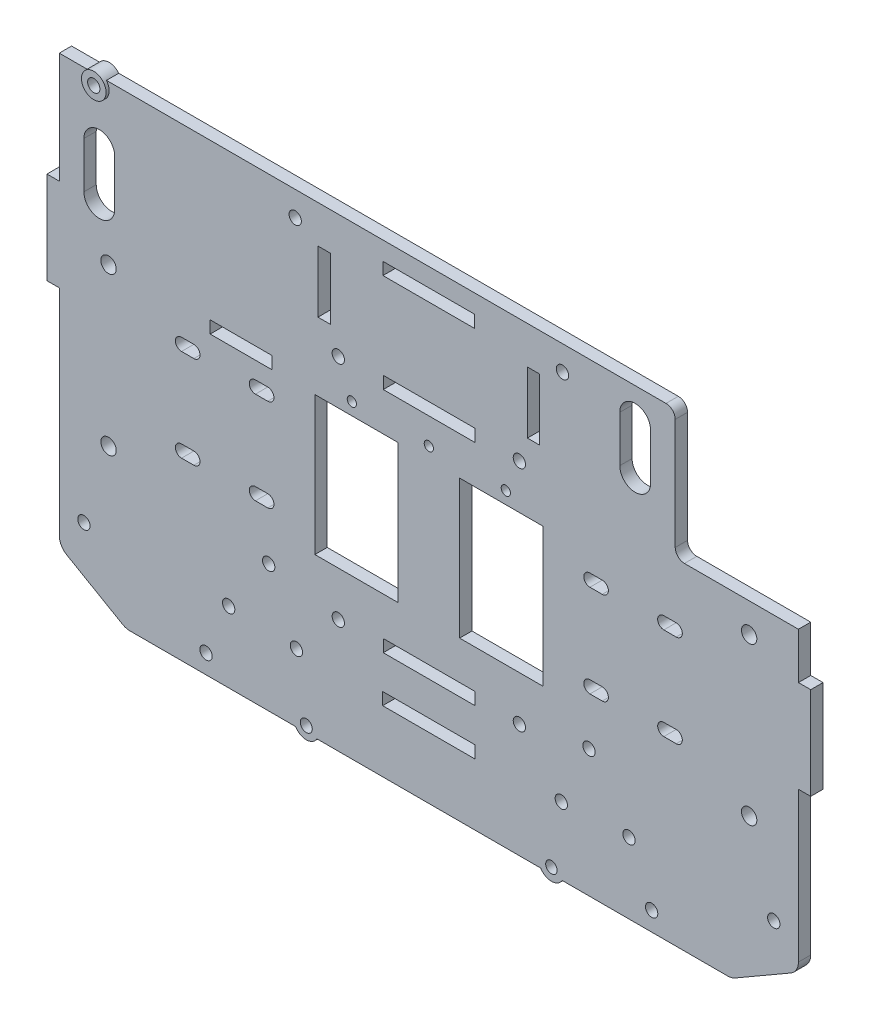
SolidWorks part; units mm, degrees
ref_plane "Front Plane" through (0, 0, 0) normal (0, 0, 1) x (1, 0, 0)
ref_plane "Top Plane" through (0, 0, 0) normal (0, 1, 0) x (1, 0, 0)
ref_plane "Right Plane" through (0, 0, 0) normal (1, 0, 0) x (0, 0, -1)
sketch "Sketch1" plane through (0, 0, 0) normal (0, 0, 1) x (1, 0, 0)
  line L1 (-120, 75.5) -> (120, 75.5)
  line L2 (-120, 75.5) -> (-120, -75.5)
  line L3 (-120, -75.5) -> (120, -75.5)
  line L4 (120, 75.5) -> (120, -75.5)
  dimension "D1" = 240
  dimension "D2" = 151
  dimension "D3" = 75.5
  dimension "D4" = 120
extrude "Boss-Extrude1" add sketch "Sketch1" along normal blind 4
sketch "Sketch2" plane through (0, 0, 0) normal (0, 0, -1) x (-1, 0, 0)
  line L4 (10, 21) -> (37, 21)
  line L5 (37, 21) -> (37, -24)
  line L6 (37, -24) -> (10, -24)
  line L7 (10, -24) -> (10, 21)
  line L8 (0, 0) -> (-98.0945, 0) construction
  line L9 (-120, 75.5) -> (120, 75.5) construction
  line L10 (120, -75.5) -> (-120, -75.5) construction
  line L11 (0, 75.5) -> (0, -75.5) construction
  line L14 (-10, -24) -> (-10, 21)
  line L15 (-37, -24) -> (-10, -24)
  line L16 (-37, 21) -> (-37, -24)
  line L17 (-10, 21) -> (-37, 21)
  dimension "D1" = 45
  dimension "D2" = 27
  dimension "D3" = 21
  dimension "D4" = 10
extrude "Cut-Extrude1" cut sketch "Sketch2" against normal blind 10
sketch "Sketch11" plane through (0, 0, 0) normal (0, 0, -1) x (-1, 0, 0)
  line L0 (0, 0) -> (-153.5827, 0) construction
  line L1 (0, 0) -> (0, 92.8663) construction
  line L2 (-120, 75.5) -> (120, 75.5) construction
  line L3 (20, 16) -> (-27, 16)
  line L4 (20, 16) -> (20, 75.5)
  line L5 (20, 75.5) -> (-27, 75.5)
  line L6 (-27, 16) -> (-27, 75.5)
  dimension "D1" = 16
  dimension "D2" = 20
  dimension "D3" = 47
extrude "Cut-Extrude8" [suppressed] cut sketch "Sketch11" against normal blind 10
sketch "Sketch12" plane through (0, 0, 0) normal (0, 0, -1) x (-1, 0, 0)
  line L0 (0, 0) -> (0, 113.3526) construction
  line L1 (0, 0) -> (164.3438, 0) construction
  circle A0 centre (23, 65) radius 2
  circle A1 centre (23, 45) radius 2
  dimension "D1" = 4
  dimension "D2" = 4
  dimension "D3" = 23
  dimension "D6" = 20
  dimension "D7" = 65
extrude "Cut-Extrude9" [suppressed] cut sketch "Sketch12" against normal blind 5
sketch "Sketch13" [suppressed] plane through (0, 0, 0) normal (0, 0, -1) x (-1, 0, 0)
  line L0 (0, 0) -> (61.643, 0) construction
  line L1 (0, 0) -> (0, 63.8684) construction
  circle A0 centre (23, 65) radius 4
  circle A1 centre (23, 45) radius 4
  circle A2 centre (23, 65) radius 2
  circle A3 centre (23, 45) radius 2
  dimension "D1" = 8
  dimension "D2" = 8
  dimension "D3" = 4
  dimension "D4" = 4
extrude "Boss-Extrude5" [suppressed] add sketch "Sketch13" against normal blind 5
ref_plane "Plane1" [suppressed] through (3.5, 0, 0) normal (1, 0, 0) x (0, 0, -1)
mirror "Mirror1" [suppressed] about plane through (3.5, 0, 0) normal (1, 0, 0)
sketch "Sketch14" plane through (0, 0, 0) normal (0, 0, -1) x (-1, 0, 0)
  line L0 (-37, -1.5) -> (-94.1401, -1.5) construction
  line L1 (-37, 21) -> (-37, -24) construction
  line L2 (-37, -1.5) -> (-37, 9.4006) construction
  line L3 (-56.3, 13.46) -> (-52.3, 13.46) construction
  line L4 (-56.3, 15.46) -> (-52.3, 15.46)
  line L5 (-56.3, 11.46) -> (-52.3, 11.46)
  line L6 (-80.3, 13.46) -> (-76.3, 13.46) construction
  line L7 (-80.3, 15.46) -> (-76.3, 15.46)
  line L8 (-80.3, 11.46) -> (-76.3, 11.46)
  line L9 (-80.3, -16.54) -> (-76.3, -16.54) construction
  line L10 (-80.3, -14.54) -> (-76.3, -14.54)
  line L11 (-80.3, -18.54) -> (-76.3, -18.54)
  line L12 (-56.3, -16.54) -> (-52.3, -16.54) construction
  line L13 (-56.3, -14.54) -> (-52.3, -14.54)
  line L14 (-56.3, -18.54) -> (-52.3, -18.54)
  line L15 (0, 0) -> (0, -41.609) construction
  line L16 (37, -1.5) -> (94.1401, -1.5) construction
  line L17 (56.3, -16.54) -> (52.3, -16.54) construction
  line L18 (56.3, -14.54) -> (52.3, -14.54)
  line L19 (56.3, -18.54) -> (52.3, -18.54)
  line L20 (80.3, -16.54) -> (76.3, -16.54) construction
  line L21 (80.3, -14.54) -> (76.3, -14.54)
  line L22 (80.3, -18.54) -> (76.3, -18.54)
  line L23 (80.3, 13.46) -> (76.3, 13.46) construction
  line L24 (80.3, 15.46) -> (76.3, 15.46)
  line L25 (80.3, 11.46) -> (76.3, 11.46)
  line L26 (56.3, 13.46) -> (52.3, 13.46) construction
  line L27 (56.3, 15.46) -> (52.3, 15.46)
  line L28 (56.3, 11.46) -> (52.3, 11.46)
  arc A0 (56.3, -14.54) -> (56.3, -18.54) centre (56.3, -16.54) cw
  arc A2 (52.3, -18.54) -> (52.3, -14.54) centre (52.3, -16.54) cw
  arc A4 (80.3, -14.54) -> (80.3, -18.54) centre (80.3, -16.54) cw
  arc A6 (76.3, -18.54) -> (76.3, -14.54) centre (76.3, -16.54) cw
  arc A8 (-56.3, 15.46) -> (-56.3, 11.46) centre (-56.3, 13.46) ccw
  arc A9 (-52.3, 11.46) -> (-52.3, 15.46) centre (-52.3, 13.46) ccw
  arc A10 (-80.3, 15.46) -> (-80.3, 11.46) centre (-80.3, 13.46) ccw
  arc A11 (-76.3, 11.46) -> (-76.3, 15.46) centre (-76.3, 13.46) ccw
  arc A12 (-80.3, -14.54) -> (-80.3, -18.54) centre (-80.3, -16.54) ccw
  arc A13 (-76.3, -18.54) -> (-76.3, -14.54) centre (-76.3, -16.54) ccw
  arc A14 (-56.3, -14.54) -> (-56.3, -18.54) centre (-56.3, -16.54) ccw
  arc A15 (-52.3, -18.54) -> (-52.3, -14.54) centre (-52.3, -16.54) ccw
  arc A16 (80.3, 15.46) -> (80.3, 11.46) centre (80.3, 13.46) cw
  arc A17 (76.3, 11.46) -> (76.3, 15.46) centre (76.3, 13.46) cw
  arc A18 (56.3, 15.46) -> (56.3, 11.46) centre (56.3, 13.46) cw
  arc A19 (52.3, 11.46) -> (52.3, 15.46) centre (52.3, 13.46) cw
  point P9 (54.3, -16.54)
  point P15 (-54.3, 13.46)
  point P22 (-78.3, 13.46)
  point P27 (-78.3, -16.54)
  point P34 (-54.3, -16.54)
  point P47 (78.3, -16.54)
  point P54 (78.3, 13.46)
  point P61 (54.3, 13.46)
  dimension "D2" = 14.96
  dimension "D3" = 15.04
  dimension "D4" = 41.3
  dimension "D5" = 4
  dimension "D6" = 4
  dimension "D7" = 4
  dimension "D8" = 4
  dimension "D9" = 41.3
  dimension "D10" = 17.3
  dimension "D11" = 4
  dimension "D12" = 4
  dimension "D13" = 4
  dimension "D14" = 4
  dimension "D15" = 17.3
extrude "Cut-Extrude10" cut sketch "Sketch14" against normal blind 5
sketch "Sketch15" plane through (0, 0, 0) normal (0, 0, -1) x (-1, 0, 0)
  line L0 (-37, -1.5) -> (-108.3455, -1.5) construction
  line L1 (-37, 21) -> (-37, -24) construction
  line L2 (0, 0) -> (0, 43.9144) construction
  line L3 (37, -1.5) -> (108.3455, -1.5) construction
  circle A1 centre (-104, -27) radius 2.5
  circle A3 centre (-104, 24) radius 2.5
  circle A4 centre (104, 24) radius 2.5
  circle A5 centre (104, -27) radius 2.5
  dimension "D1" = 5
  dimension "D2" = 5
  dimension "D3" = 25.5
  dimension "D4" = 25.5
  dimension "D5" = 104
extrude "Cut-Extrude11" cut sketch "Sketch15" against normal blind 10
sketch "Sketch16" plane through (0, 0, 0) normal (0, 0, -1) x (-1, 0, 0)
  line L0 (0, 0) -> (113.7141, 0) construction
  line L1 (0, 0) -> (0, 64.2652) construction
  circle A1 centre (59.5, 57.4178) radius 2
  circle A3 centre (59.5, 37.4178) radius 2
  circle A5 centre (59.5, 17.4178) radius 2
  dimension "D1" = 4
  dimension "D2" = 4
  dimension "D3" = 4
  dimension "D4" = 59.5
  dimension "D5" = 17.4178
  dimension "D6" = 20
  dimension "D7" = 20
extrude "Cut-Extrude12" [suppressed] cut sketch "Sketch16" against normal blind 10
sketch "Sketch17" plane through (0, 0, 0) normal (0, 0, -1) x (-1, 0, 0)
  line L0 (0, 0) -> (61.7311, 0) construction
  line L1 (0, 0) -> (0, 40.2669) construction
  line L2 (15, 33.5) -> (15, 38.7)
  line L7 (-15, 38.7) -> (15, 38.7)
  line L8 (-15, 33.5) -> (-15, 38.7)
  line L9 (-15, 33.5) -> (15, 33.5)
  line L12 (-15, -36.5) -> (15, -36.5)
  line L13 (-15, -36.5) -> (-15, -41.7)
  line L14 (-15, -41.7) -> (15, -41.7)
  line L15 (15, -36.5) -> (15, -41.7)
  circle A0 centre (-29.9, -39.1) radius 2
  circle A1 centre (29.9, -39.1) radius 2
  circle A2 centre (-29.9, 36.1) radius 2
  circle A3 centre (29.9, 36.1) radius 2
  point P25 (-15, 36.1)
  point P27 (-15, -39.1)
  dimension "D10" = 4
  dimension "D11" = 4
  dimension "D12" = 4
  dimension "D13" = 4
  dimension "D1" = 33.5
  dimension "D2" = 15
  dimension "D3" = 90
  dimension "D4" = 30
  dimension "D5" = 5.2
  dimension "D6" = 36.5
  dimension "D7" = 5.2
  dimension "D8" = 15
  dimension "D9" = 30
  dimension "D14" = 14.9
  dimension "D15" = 14.9
  dimension "D16" = 14.9
  dimension "D17" = 14.9
extrude "Cut-Extrude13" [suppressed] cut sketch "Sketch17" against normal blind 10
sketch "Sketch20" plane through (0, 0, 0) normal (0, 0, -1) x (-1, 0, 0)
  line L12 (0, 0) -> (0, 66.2601) construction
  line L13 (0, 0) -> (-22.6234, 0) construction
  circle A0 centre (43.2, 67) radius 2
  circle A1 centre (-43.2, 67) radius 2
  point P15 (-11.3117, 0)
  dimension "D1" = 4
  dimension "D2" = 4
  dimension "D3" = 43.2
  dimension "D4" = 67
  dimension "D5" = 43.2
  dimension "D6" = 67
extrude "Cut-Extrude15" [suppressed] cut sketch "Sketch20" against normal blind 5
sketch "Sketch23" plane through (0, 0, 0) normal (0, 0, -1) x (-1, 0, 0)
  line L8 (0, 0) -> (0, -64.892) construction
  line L9 (0, 0) -> (29.1708, 0) construction
  circle A0 centre (42.8, -54) radius 2
  circle A1 centre (-42.8, -54) radius 2
  dimension "D1" = 4
  dimension "D2" = 54
  dimension "D3" = 42.8
extrude "Cut-Extrude16" [suppressed] cut sketch "Sketch23" against normal blind 5
sketch "Sketch24" plane through (0, 0, 0) normal (0, 0, -1) x (-1, 0, 0)
  line L1 (-15.1, -56.7) -> (15.1, -56.7)
  line L3 (-15.1, -51.5) -> (-15.1, -56.7)
  line L6 (15.1, -51.5) -> (15.1, -56.7)
  line L7 (-15.1, -51.5) -> (15.1, -51.5)
  line L8 (0, 0) -> (0, -47.2629) construction
  line L9 (0, 0) -> (-25.5979, 0) construction
  dimension "D1" = 51.5
  dimension "D2" = 5.2
  dimension "D3" = 15.1
  dimension "D4" = 15.1
extrude "Cut-Extrude17" [suppressed] cut sketch "Sketch24" against normal blind 5
sketch "Sketch27" plane through (0, 0, 0) normal (0, 0, -1) x (-1, 0, 0)
  line L0 (0, 0) -> (0, 10.7303) construction
  line L1 (0, 0) -> (-15.1095, 0) construction
  circle A1 centre (-25, 25) radius 1.5
  circle A3 centre (0, 25) radius 1.5
  circle A5 centre (25, 25) radius 1.5
  dimension "D1" = 3
  dimension "D2" = 3
  dimension "D3" = 3
  dimension "D4" = 25
  dimension "D5" = 25
  dimension "D6" = 25
extrude "Cut-Extrude20" cut sketch "Sketch27" against normal blind 10
sketch "Sketch28" plane through (0, 0, 4) normal (0, 0, 1) x (1, 0, 0)
  line L0 (0, 0) -> (0, -94.1859) construction
  line L1 (0, 0) -> (142.2431, 0) construction
  circle A1 centre (112, -52.5) radius 2
  circle A3 centre (65, -52.5) radius 2
  circle A4 centre (-65, -52.5) radius 2
  circle A5 centre (-112, -52.5) radius 2
  dimension "D2" = 4
  dimension "D3" = 4
  dimension "D1" = 47
  dimension "D4" = 65
  dimension "D5" = 52.5
extrude "Cut-Extrude21" cut sketch "Sketch28" against normal blind 10
sketch "Sketch29" plane through (0, 0, 0) normal (0, 0, -1) x (-1, 0, 0)
  line L1 (0, 0) -> (0, 54.3151) construction
  line L3 (0, 0) -> (50.4832, 0) construction
  circle A0 centre (62, 21.5) radius 2
  dimension "D1" = 4
  dimension "D2" = 21.5
  dimension "D3" = 62
extrude "Cut-Extrude22" [suppressed] cut sketch "Sketch29" against normal blind 10
sketch "Sketch30" plane through (0, 0, 0) normal (0, 0, -1) x (-1, 0, 0)
  line L1 (0, 0) -> (31.6548, 0) construction
  line L3 (0, 0) -> (0, -25.192) construction
  circle A0 centre (-24.8, -29.5) radius 2
  circle A1 centre (24.8, -29.5) radius 2
  dimension "D1" = 4
  dimension "D2" = 4
  dimension "D3" = 24.8
  dimension "D4" = 24.8
  dimension "D5" = 29.5
extrude "Cut-Extrude23" [suppressed] cut sketch "Sketch30" against normal blind 10
sketch "Sketch31" plane through (0, 0, 0) normal (0, 0, -1) x (-1, 0, 0)
  line L0 (0, 0) -> (0, -47.0899) construction
  line L1 (0, 0) -> (74.357, 0) construction
  circle A2 centre (72.3457, -69.3397) radius 2
  circle A5 centre (-72.3457, -69.3397) radius 2
  dimension "D1" = 72.3457
  dimension "D2" = 4
  dimension "D3" = 69.3397
extrude "Cut-Extrude24" cut sketch "Sketch31" against normal blind 10
sketch "Sketch32" plane through (0, 0, 0) normal (0, 0, -1) x (-1, 0, 0)
  line L0 (0, 0) -> (0, -27.0563) construction
  line L1 (0, 0) -> (46.0859, 0) construction
  circle A1 centre (52.0058, -34.11) radius 2
  circle A2 centre (-52.0058, -34.11) radius 2
  dimension "D1" = 4
  dimension "D2" = 34.11
  dimension "D3" = 52.0058
extrude "Cut-Extrude25" cut sketch "Sketch32" against normal blind 10
sketch "Sketch34" plane through (0, 0, 0) normal (0, 0, -1) x (-1, 0, 0)
  line L0 (-120, -75.5) -> (-120, 75.5) construction
  line L1 (-120, 75.5) -> (-80, 75.5)
  line L2 (-120, 75.5) -> (-120, 33.5)
  line L3 (-120, 33.5) -> (-80, 33.5)
  line L4 (-80, 75.5) -> (-80, 33.5)
  line L7 (-120, 75.5) -> (120, 75.5) construction
  dimension "D1" = 42
  dimension "D3" = 40
extrude "Cut-Extrude26" cut sketch "Sketch34" against normal blind 10
sketch "Sketch35" plane through (0, 0, 0) normal (0, 0, -1) x (-1, 0, 0)
  line L0 (-49.5, 37.5) -> (-69.5, 37.5) construction
  line L1 (-49.5, 32.5) -> (-69.5, 32.5)
  line L2 (-49.5, 42.5) -> (-69.5, 42.5)
  line L3 (-120, -75.5) -> (-120, 33.5) construction
  line L4 (-80, 75.5) -> (120, 75.5) construction
  arc A0 (-49.5, 32.5) -> (-49.5, 42.5) centre (-49.5, 37.5) ccw
  arc A1 (-69.5, 42.5) -> (-69.5, 32.5) centre (-69.5, 37.5) ccw
  point P2 (-59.5, 37.5)
  dimension "D1" = 10
  dimension "D2" = 60.5
  dimension "D3" = 33
  dimension "D4" = 20
extrude "Cut-Extrude27" [suppressed] cut sketch "Sketch35" against normal blind 10
sketch "Sketch36" plane through (0, 0, 0) normal (0, 0, -1) x (-1, 0, 0)
  line L0 (107, 40.5) -> (107, 55.5) construction
  line L1 (102, 40.5) -> (102, 55.5)
  line L2 (112, 40.5) -> (112, 55.5)
  line L3 (120, 75.5) -> (120, -75.5) construction
  line L4 (-80, 75.5) -> (120, 75.5) construction
  arc A0 (102, 40.5) -> (112, 40.5) centre (107, 40.5) ccw
  arc A1 (112, 55.5) -> (102, 55.5) centre (107, 55.5) ccw
  point P2 (107, 48)
  dimension "D1" = 15
  dimension "D2" = 8
  dimension "D3" = 10
  dimension "D4" = 20
extrude "Cut-Extrude28" cut sketch "Sketch36" against normal blind 10
sketch "Sketch37" plane through (0, 0, 4) normal (0, 0, 1) x (1, 0, 0)
  line L1 (36, 43.25) -> (36, 63.25)
  line L3 (36, 63.25) -> (31, 63.25)
  line L5 (31, 43.25) -> (31, 63.25)
  line L7 (36, 43.25) -> (31, 43.25)
  line L8 (0, 0) -> (0, 66.0689) construction
  line L9 (-36, 43.25) -> (-31, 43.25)
  line L10 (-31, 43.25) -> (-31, 63.25)
  line L11 (-36, 63.25) -> (-31, 63.25)
  line L12 (-36, 43.25) -> (-36, 63.25)
  line L13 (0, 0) -> (45.9308, 0) construction
  dimension "D1" = 5
  dimension "D2" = 20
  dimension "D3" = 43.25
  dimension "D4" = 31
extrude "Cut-Extrude29" [suppressed] cut sketch "Sketch37" against normal blind 10
sketch "Sketch38" plane through (0, 0, 4) normal (0, 0, 1) x (1, 0, 0)
  line L0 (80, 75.5) -> (-120, 75.5) construction
  line L1 (-120, 75.5) -> (-120, -75.5) construction
  line L4 (-50.8, 26.02) -> (-50.8, 21)
  line L5 (-71, 21) -> (-50.8, 21)
  line L6 (-71, 26.02) -> (-71, 21)
  line L7 (-71, 26.02) -> (-50.8, 26.02)
  dimension "D1" = 5.02
  dimension "D2" = 20.2
  dimension "D3" = 49.48
  dimension "D4" = 49
extrude "Cut-Extrude30" [suppressed] cut sketch "Sketch38" against normal blind 5
sketch "Sketch39" plane through (0, 0, 0) normal (0, 0, -1) x (-1, 0, 0)
  circle A0 centre (107.8, 73) radius 2
  dimension "D1" = 4
extrude "Cut-Extrude31" cut sketch "Sketch39" against normal blind 5
sketch "Sketch40" plane through (0, 0, 0) normal (0, 0, -1) x (-1, 0, 0)
  circle A0 centre (107.8, 73) radius 2
  circle A1 centre (107.8, 73) radius 4
  dimension "D1" = 8
extrude "Boss-Extrude6" add sketch "Sketch40" against normal blind 5
fillet "Fillet1" radius 3 1 edges at (80, 33.5, 2)
sketch "Sketch41" plane through (0, 0, 0) normal (0, 0, -1) x (-1, 0, 0)
  circle A0 centre (39.8, -73) radius 2
  circle A1 centre (-39.8, -73) radius 2
  dimension "D1" = 4
  dimension "D2" = 4
extrude "Cut-Extrude32" [suppressed] cut sketch "Sketch41" against normal blind 5
sketch "Sketch42" [suppressed] plane through (0, 0, 0) normal (0, 0, -1) x (-1, 0, 0)
  circle A0 centre (-39.8, -73) radius 2
  circle A1 centre (-39.8, -73) radius 4
  circle A2 centre (39.8, -73) radius 2
  circle A3 centre (39.8, -73) radius 4
  dimension "D1" = 4
  dimension "D2" = 8
  dimension "D3" = 4
  dimension "D4" = 8
extrude "Boss-Extrude7" [suppressed] add sketch "Sketch42" against normal blind 4
sketch "Sketch43" plane through (0, 0, 0) normal (0, 0, -1) x (-1, 0, 0)
  line L0 (-120, -75.5) -> (-120, 33.5) construction
  line L1 (-120, 18.5) -> (-124, 18.5)
  line L2 (-120, 18.5) -> (-120, -11.5)
  line L3 (-120, -11.5) -> (-124, -11.5)
  line L4 (-124, 18.5) -> (-124, -11.5)
  line L5 (120, 75.5) -> (120, -75.5) construction
  line L10 (120, -75.5) -> (-120, -75.5) construction
  line L11 (120, 39.5) -> (124, 39.5)
  line L12 (120, 39.5) -> (120, 9.5)
  line L13 (120, 9.5) -> (124, 9.5)
  line L14 (124, 39.5) -> (124, 9.5)
  line L15 (120, -75.5) -> (-120, -75.5) construction
  point P16 (-120, 3.5)
  dimension "D1" = 4
  dimension "D2" = 64
  dimension "D3" = 30
  dimension "D4" = 85
  dimension "D5" = 30
  dimension "D6" = 4
extrude "Boss-Extrude8" add sketch "Sketch43" against normal blind 4
fillet "Fillet2" radius 3 1 edges at (80, 75.5, 2)
sketch "Sketch44" plane through (0, 0, 0) normal (0, 0, -1) x (-1, 0, 0)
  line L0 (120, -75.5) -> (-120, -75.5) construction
  line L1 (-98.3172, -75.5016) -> (-120, -62.9831)
  line L2 (120, -75.5) -> (-120, -75.5) construction
  line L3 (98.3172, -75.5016) -> (120, -62.9831)
  line L4 (120, 9.5) -> (120, -75.5) construction
  line L5 (-120, -75.5) -> (-120, -11.5) construction
  line L6 (-120, -62.9831) -> (-120, -75.5)
  line L7 (-120, -75.5) -> (-98.3172, -75.5016)
  line L8 (98.3172, -75.5016) -> (120, -75.5)
  line L9 (120, -75.5) -> (120, -62.9831)
  dimension "D1" = 30
  dimension "D2" = 30
extrude "Cut-Extrude33" cut sketch "Sketch44" against normal blind 10
fillet "Fillet4" radius 5 4 edges at (-120, -62.9831, 2) (-98.32, -75.5, 2) (120, -62.9831, 2) (98.32, -75.5, 2)
sketch "Sketch45" plane through (0, 0, 0) normal (0, 0, -1) x (-1, 0, 0)
  line L0 (-67, 65.5) -> (-67, 50.5) construction
  line L1 (-62, 65.5) -> (-62, 50.5)
  line L2 (-72, 65.5) -> (-72, 50.5)
  line L3 (-80, 36.5) -> (-80, 72.5) construction
  line L4 (-77, 75.5) -> (104.6775, 75.5) construction
  arc A0 (-62, 65.5) -> (-72, 65.5) centre (-67, 65.5) ccw
  arc A1 (-72, 50.5) -> (-62, 50.5) centre (-67, 50.5) ccw
  point P2 (-67, 58)
  point P7 (-62, 58)
  dimension "D1" = 10
  dimension "D2" = 8
  dimension "D3" = 10
  dimension "D4" = 15
extrude "Cut-Extrude34" cut sketch "Sketch45" against normal blind 5
sketch "Sketch46" plane through (0, 0, 0) normal (0, 0, -1) x (-1, 0, 0)
  line L16 (-15, -51.5) -> (-15, -55.5)
  line L17 (-15, -51.5) -> (15, -51.5)
  line L18 (-15, -55.5) -> (15, -55.5)
  line L19 (15, -51.5) -> (15, -55.5)
  line L20 (-15, -36.5) -> (-15, -40.5)
  line L21 (14.8, -36.5) -> (14.8, -40.5)
  line L22 (-15, -40.5) -> (14.8, -40.5)
  line L23 (-15, -36.5) -> (14.8, -36.5)
  line L24 (-15, 37.5) -> (-15, 33.5)
  line L25 (-15, 37.5) -> (14.8, 37.5)
  line L26 (-15, 33.5) -> (14.8, 33.5)
  line L27 (14.8, 37.5) -> (14.8, 33.5)
  line L28 (-14.9, 65.5) -> (-14.9, 69.5)
  line L29 (-14.9, 69.5) -> (14.9, 69.5)
  line L30 (14.9, 65.5) -> (14.9, 69.5)
  line L31 (-14.9, 65.5) -> (14.9, 65.5)
extrude "Cut-Extrude35" cut sketch "Sketch46" against normal blind 10
sketch "Sketch47" plane through (0, 0, 0) normal (0, 0, -1) x (-1, 0, 0)
  circle A4 centre (29.4, 35.5) radius 2
  circle A5 centre (-29.4, 35.5) radius 2
  circle A6 centre (-43.4, 67.5) radius 2
  circle A7 centre (43.4, 67.5) radius 2
  circle A12 centre (29.4, -38.5) radius 2
  circle A13 centre (-29.4, -38.5) radius 2
  circle A14 centre (43, -53.5) radius 2
  circle A15 centre (-43, -53.5) radius 2
extrude "Cut-Extrude36" cut sketch "Sketch47" against normal blind 10
sketch "Sketch48" plane through (0, 0, 0) normal (0, 0, -1) x (-1, 0, 0)
  circle A0 centre (-39.8, -73.5) radius 1.995
  circle A1 centre (39.8, -73.5) radius 1.995
  dimension "D1" = 3.99
  dimension "D2" = 3.99
extrude "Cut-Extrude37" cut sketch "Sketch48" against normal blind 10
sketch "Sketch49" plane through (0, 0, 0) normal (0, 0, -1) x (-1, 0, 0)
  circle A0 centre (-39.8, -73.5) radius 1.8681
  circle A1 centre (-39.8, -73.5) radius 4
  circle A2 centre (39.8, -73.5) radius 1.95
  circle A3 centre (39.8, -73.5) radius 4
  dimension "D1" = 8
  dimension "D2" = 8
extrude "Boss-Extrude9" add sketch "Sketch49" against normal blind 4
sketch "Sketch50" plane through (0, 0, 4) normal (0, 0, 1) x (1, 0, 0)
  line L0 (-51, 25) -> (-51, 21) construction
  line L1 (-71, 21) -> (-51, 21) construction
  line L2 (-71, 25) -> (-51, 25) construction
  line L3 (-71, 25) -> (-71, 21) construction
  line L4 (-51, 25) -> (-51, 21)
  line L5 (-71, 21) -> (-51, 21)
  line L6 (-71, 25) -> (-51, 25)
  line L7 (-71, 25) -> (-71, 21)
extrude "Cut-Extrude38" cut sketch "Sketch50" against normal blind 10
sketch "Sketch51" plane through (0, 0, 0) normal (0, 0, -1) x (-1, 0, 0)
  line L0 (-36, 63.25) -> (-32, 63.25) construction
  line L1 (-36, 43.25) -> (-32, 43.25) construction
  line L2 (-32, 63.25) -> (-32, 43.25) construction
  line L3 (-36, 63.25) -> (-36, 43.25) construction
  line L4 (32, 63.25) -> (36, 63.25) construction
  line L5 (32, 63.25) -> (32, 43.25) construction
  line L6 (32, 43.25) -> (36, 43.25) construction
  line L7 (36, 63.25) -> (36, 43.25) construction
  line L8 (-36, 63.25) -> (-32, 63.25)
  line L9 (-36, 43.25) -> (-32, 43.25)
  line L10 (-32, 63.25) -> (-32, 43.25)
  line L11 (-36, 63.25) -> (-36, 43.25)
  line L12 (32, 63.25) -> (36, 63.25)
  line L13 (32, 63.25) -> (32, 43.25)
  line L14 (32, 43.25) -> (36, 43.25)
  line L15 (36, 63.25) -> (36, 43.25)
extrude "Cut-Extrude39" cut sketch "Sketch51" against normal blind 10
